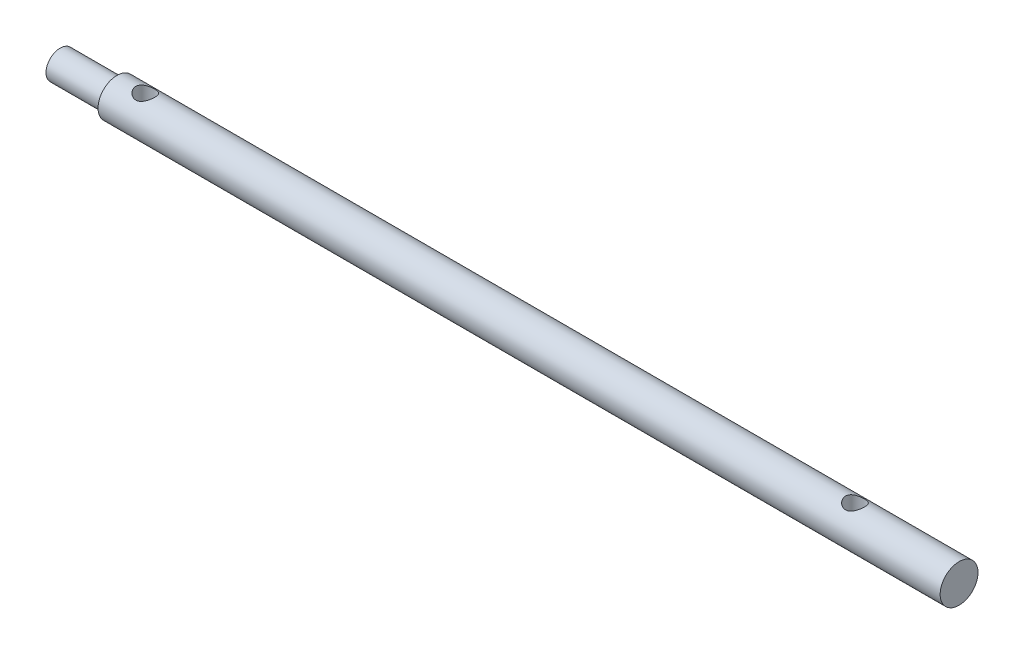
SolidWorks part; units mm, degrees
ref_plane "Front Plane" through (0, 0, 0) normal (0, 0, 1) x (1, 0, 0)
ref_plane "Top Plane" through (0, 0, 0) normal (0, 1, 0) x (1, 0, 0)
ref_plane "Right Plane" through (0, 0, 0) normal (1, 0, 0) x (0, 0, -1)
sketch "Sketch1" plane through (0, 0, 0) normal (0, 0, 1) x (1, 0, 0)
  line L0 (-16.5039, 0) -> (96.0621, 0) construction
  line L3 (0, 1.5) -> (-6, 1.5)
  line L4 (-6, 0) -> (-6, 1.5)
  line L5 (-3, 0) -> (-6, 1.5) construction
  line L6 (0, 1.5) -> (-3, 0) construction
  line L8 (89, 0) -> (89, 2)
  line L9 (89, 2) -> (0, 2)
  line L11 (44.5, 0) -> (0, 2) construction
  line L12 (89, 2) -> (44.5, 0) construction
  line L13 (0, 1.5) -> (0, 2)
  line L14 (-6, 0) -> (89, 0)
  point P0 (-3, 0)
  point P7 (44.5, 0)
  dimension "D1" = 6
  dimension "D2" = 89
  dimension "D3" = 1.5
  dimension "D4" = 2
revolve "Revolve1" add sketch "Sketch1" angle 360 about L14
sketch "Sketch3" plane through (0, 0, 0) normal (0, 1, 0) x (1, 0, 0)
  line L0 (89, -2) -> (89, 2) construction
  circle A0 centre (3, 0) radius 1
  circle A1 centre (78, 0) radius 1
  point P7 (0, 0)
  dimension "D1" = 2
  dimension "D3" = 2
  dimension "D2" = 3
  dimension "D4" = 11
extrude "Cut-Extrude1" cut sketch "Sketch3" against normal through all both and the other way through all
